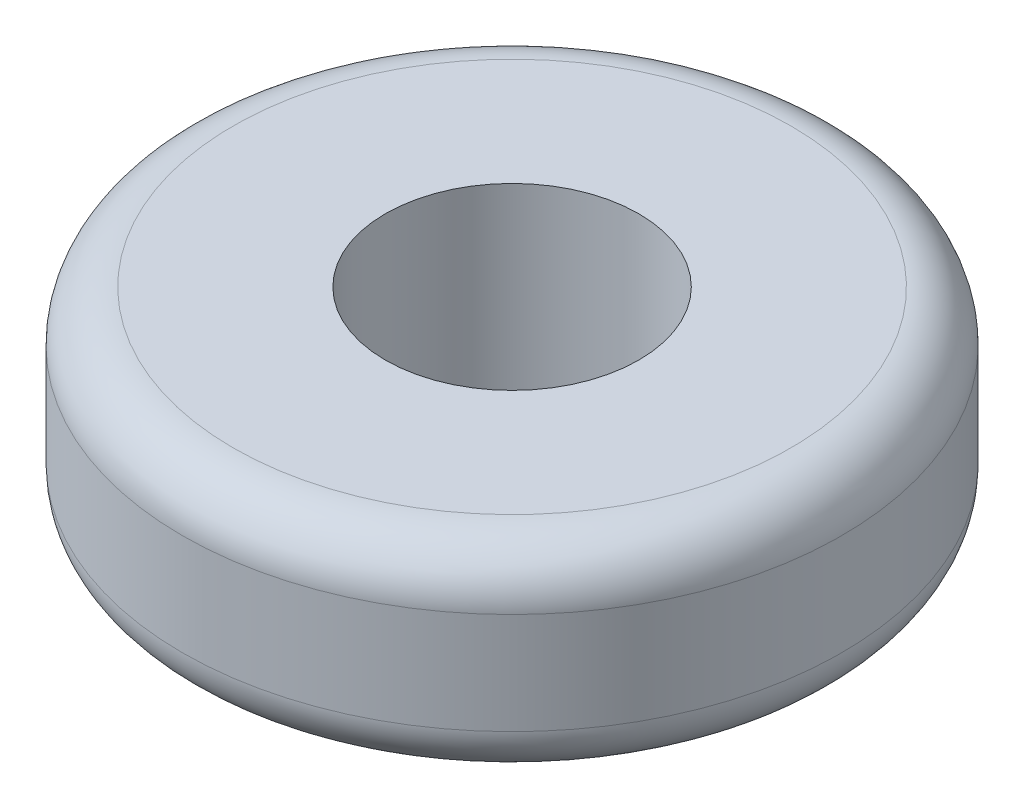
SolidWorks part; units mm, degrees
ref_plane "Front Plane" through (0, 0, 0) normal (0, 0, 1) x (1, 0, 0)
ref_plane "Top Plane" through (0, 0, 0) normal (0, 1, 0) x (1, 0, 0)
ref_plane "Right Plane" through (0, 0, 0) normal (1, 0, 0) x (0, 0, -1)
sketch "Sketch1" plane through (0, 0, 0) normal (0, 1, 0) x (1, 0, 0)
  circle A0 centre (0, 0) radius 13
  circle A1 centre (0, 0) radius 5
extrude "Boss-Extrude1" add sketch "Sketch1" along normal blind 8
fillet "Fillet1" radius 2 2 edges at (0, 0, 13) (0, 8, 13)
